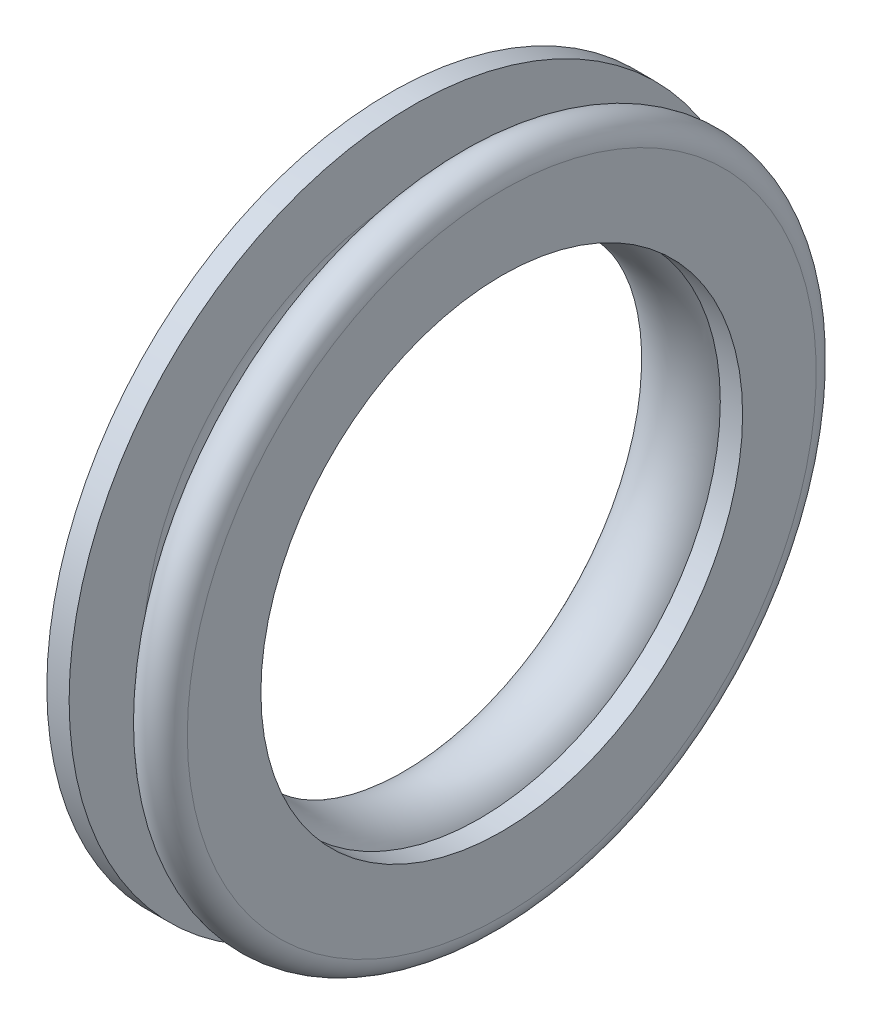
SolidWorks part; units mm, degrees
ref_plane "Front Plane" through (0, 0, 0) normal (0, 0, 1) x (1, 0, 0)
ref_plane "Top Plane" through (0, 0, 0) normal (0, 1, 0) x (1, 0, 0)
ref_plane "Right Plane" through (0, 0, 0) normal (1, 0, 0) x (0, 0, -1)
sketch "Sketch2" plane through (0, 0, 0) normal (0, 0, 1) x (1, 0, 0)
  line L0 (0, 7.7) -> (0, 0) construction
  line L1 (0, 0) -> (8.9235, 0) construction
  line L2 (0, 7.7) -> (0, 6.05)
  line L3 (2, 6.05) -> (2, 7.05) construction
  line L4 (2.5, 7.05) -> (2.5, 5.4)
  line L5 (0.5, 7.7) -> (0.5, 6.05)
  line L6 (1.5, 6.05) -> (1.5, 7.05)
  line L7 (2, 7.05) -> (2, 5.4) construction
  line L8 (2, 5.4) -> (2.5, 5.4)
  line L9 (2, 7.05) -> (1.5, 7.05) construction
  line L10 (2, 6.05) -> (2, 5.4)
  line L11 (0, 7.7) -> (0.5, 7.7)
  arc A0 (0, 6.05) -> (2, 6.05) centre (1, 6.05) ccw
  arc A1 (1.5, 7.05) -> (2.5, 7.05) centre (2, 7.05) cw
  arc A2 (0.5, 6.05) -> (1.5, 6.05) centre (1, 6.05) ccw
  dimension "D3" = 1
  dimension "D5" = 0.5
  dimension "D1" = 7.7
  dimension "D2" = 1.65
  dimension "D4" = 1
  dimension "D6" = 1.65
  dimension "D7" = 0.5
  dimension "D8" = 0.5
revolve "Revolve1" add sketch "Sketch2" angle 360 about L1
